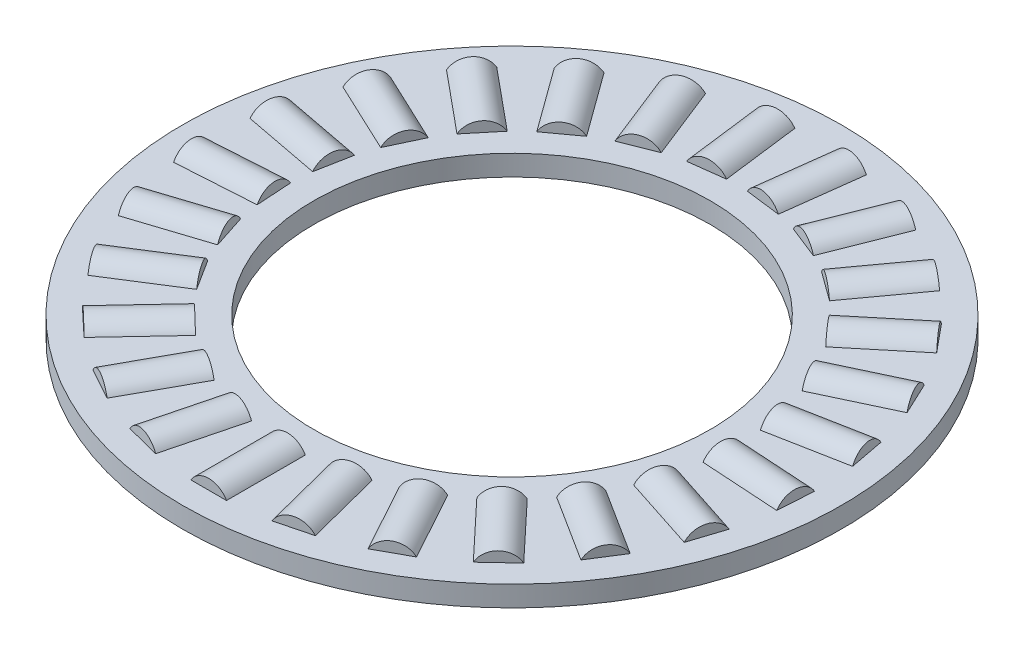
SolidWorks part; units mm, degrees
material "AISI 304"
ref_plane "Front Plane" through (0, 0, 0) normal (0, 0, 1) x (1, 0, 0)
ref_plane "Top Plane" through (0, 0, 0) normal (0, 1, 0) x (1, 0, 0)
ref_plane "Right Plane" through (0, 0, 0) normal (1, 0, 0) x (0, 0, -1)
sketch "Sketch1" plane through (0, 0, 0) normal (1, 0, 0) x (0, 0, -1)
  line L0 (-15.875, 0) -> (15.875, 0) construction
  line L1 (0, -0.9922) -> (0, 0.9922) construction
  line L2 (-15.875, 0.4961) -> (-9.5504, 0.4961)
  line L3 (-15.875, 0.4961) -> (-15.875, -0.4961)
  line L4 (-15.875, -0.4961) -> (-9.5504, -0.4961)
  line L5 (-9.5504, 0.4961) -> (-9.5504, -0.4961)
  line L7 (-12.7127, 0.9922) -> (-12.7127, 0.4961) construction
  line L8 (-14.6101, 0.9922) -> (-10.8153, 0.9922) construction
  line L9 (-14.6101, 0.9922) -> (-14.6101, -0.9922) construction
  line L10 (-14.6101, -0.9922) -> (-10.8153, -0.9922) construction
  line L11 (-10.8153, 0.9922) -> (-10.8153, -0.9922) construction
  line L12 (15.875, 0.9922) -> (15.875, -0.9922) construction
  point P16 (-14.6101, 0)
  point P21 (15.875, 0)
  dimension "OD" = 31.75
  dimension "ID" = 19.1008
  dimension "Washer Thickness" = 0.9922
  dimension "D1" = 3.7948
  dimension "Thickness" = 1.9844
sketch "Sketch6" plane through (0, 0, 0) normal (0, 1, 0) x (1, 0, 0)
  circle A0 centre (0, 0) radius 15.875 construction
  circle A1 centre (0, 0) radius 9.5504 construction
  circle A2 centre (0, 0) radius 9.525 construction
  dimension "For Shaft Diameter" = 19.05
  dimension "OD" = 31.75
  dimension "ID" = 19.1008
sketch "Sketch5" plane through (0, 0, 0) normal (1, 0, 0) x (0, 0, -1)
  line L1 (-15.875, 0.4961) -> (-9.5504, 0.4961)
  line L2 (-15.875, 0.4961) -> (-15.875, -0.4961)
  line L3 (-15.875, -0.4961) -> (-9.5504, -0.4961)
  line L4 (-9.5504, 0.4961) -> (-9.5504, -0.4961)
revolve "Revolve3" add sketch "Sketch5" angle 360 about L1
sketch "Sketch3" plane through (0, 0, 0) normal (1, 0, 0) x (0, 0, -1)
  line L0 (-14.6101, 0.9922) -> (-14.6101, -0.9922) construction
  line L1 (-14.6101, 0) -> (-10.8153, 0)
  line L2 (-14.6101, 0) -> (-14.6101, 0.9922)
  line L3 (-14.6101, 0.9922) -> (-10.8153, 0.9922)
  line L4 (-10.8153, 0) -> (-10.8153, 0.9922)
revolve "Cut-Revolve1" cut sketch "Sketch3" angle 360 about L1
sketch "Sketch2" plane through (0, 0, 0) normal (1, 0, 0) x (0, 0, -1)
  line L1 (-14.6101, 0) -> (-10.8153, 0)
  line L2 (-14.6101, 0) -> (-14.6101, 0.9922)
  line L3 (-14.6101, 0.9922) -> (-10.8153, 0.9922)
  line L4 (-10.8153, 0) -> (-10.8153, 0.9922)
revolve "Revolve2" add sketch "Sketch2" angle 360 about L1
ref_axis "Axis1" through (0, 0.9922, 0) along (0, -1, 0)
pattern_circular "CirPattern1" count 25 every 14.4 about axis through (0, 0.9922, 0) along (0, -1, 0) of bodies 187 411
pattern_circular "CirPattern2" count 25 every 14.4 about axis through (0, 0, 0) along (0, 1, 0) of "Cut-Revolve1"
equation "\"Rollers@CirPattern1\"= \"OD@Sketch1\" * 20"
equation "\"Angle@CirPattern1\" = 360/\"Rollers@CirPattern1\""
equation "\"D1@CirPattern2\" = \"Rollers@CirPattern1\""
equation "\"D2@CirPattern2\" = \"Angle@CirPattern1\""
equation "\"D1@Sketch1\"=((\"OD@Sketch1\"-\"ID@Sketch1\")/2)*.6"
